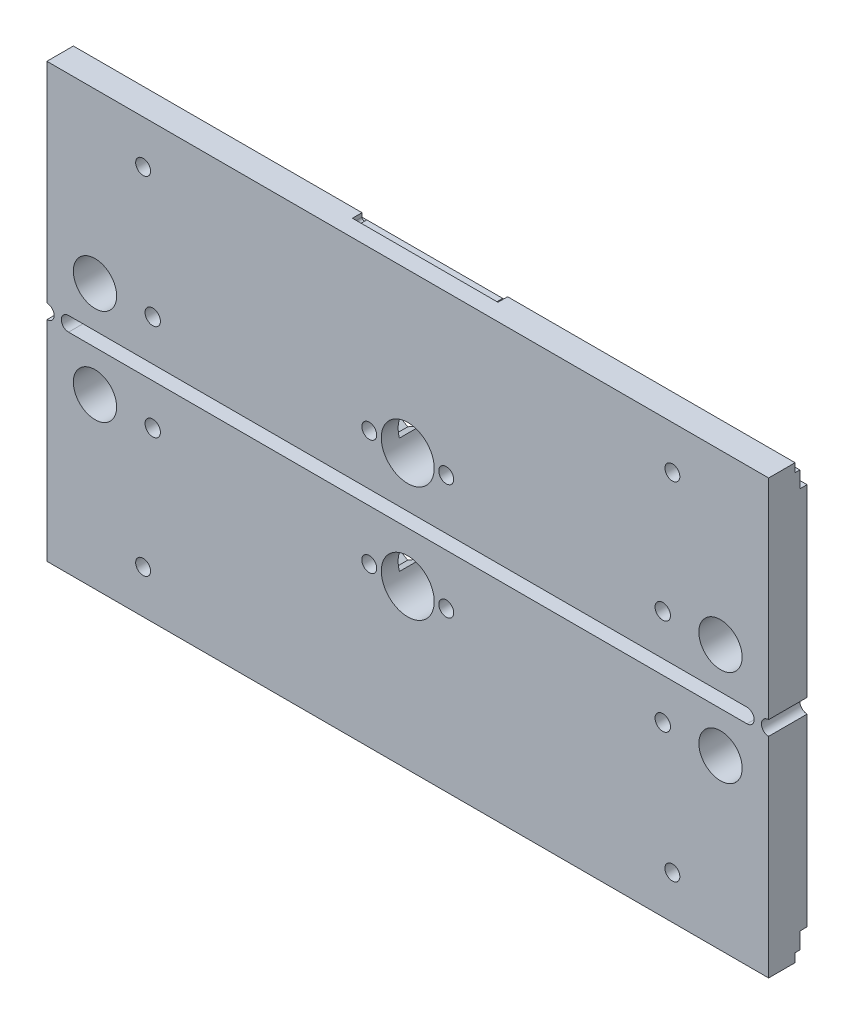
SolidWorks part; units mm, degrees
ref_plane "前视基准面" through (0, 0, 0) normal (0, 0, 1) x (1, 0, 0)
ref_plane "上视基准面" through (0, 0, 0) normal (0, 1, 0) x (1, 0, 0)
ref_plane "右视基准面" through (0, 0, 0) normal (1, 0, 0) x (0, 0, -1)
sketch "前视图草图" plane through (0, 0, 0) normal (0, 0, 1) x (1, 0, 0)
  line L0 (0, 0) -> (8.5179, 0) construction
  line L1 (0, 0) -> (0, 5.4227) construction
sketch "草图2" plane through (0, 0, 0) normal (0, 0, 1) x (1, 0, 0)
  line L0 (0, 0) -> (150, 0)
  line L1 (-200000, 0) -> (200008.5179, 0) construction
  line L2 (150, 0) -> (150, 43.5)
  line L3 (150, 43.5) -> (0, 43.5)
  line L4 (0, -200000) -> (0, 200005.4227) construction
  line L5 (0, 43.5) -> (0, 0)
  line L6 (75, 43.5) -> (75, 0) construction
  line L7 (10, 8.5) -> (140, 8.5) construction
  circle A0 centre (10, 8.5) radius 4.5
  circle A1 centre (75, 10.5) radius 4.05
  circle A2 centre (140, 8.5) radius 4.5
  dimension "D3" = 2
  dimension "D9" = 9
  dimension "D10" = 9
  dimension "D11" = 8.1
  dimension "D1" = 43.5
  dimension "D2" = 150
  dimension "D4" = 65
  dimension "D6" = 65
  dimension "D7" = 8.5
  dimension "D8" = 10
  dimension "D12" = 10
extrude "凸台-拉伸1" add sketch "草图2" along normal blind 8
sketch "草图3" plane through (0, 0, 8) normal (0, 0, 1) x (1, 0, 0)
  line L0 (16.088, 8) -> (31.4805, 8) construction
  line L1 (10, 8.5) -> (10, 17.3386) construction
  line L2 (140, 8.5) -> (140, 17.0917) construction
  line L4 (-200000, 0) -> (200008.5179, 0) construction
  circle A2 centre (26, 8) radius 2.55
  circle A3 centre (124, 8) radius 2.55
  dimension "D4" = 5.1
  dimension "D5" = 5.1
  dimension "D1" = 8
  dimension "D2" = 16
  dimension "D3" = 16
extrude "切除-拉伸1" [suppressed] cut sketch "草图3" against normal through all
sketch "草图4" plane through (150, 0, 0) normal (1, 0, 0) x (0, 0, -1)
  line L1 (0, -200000) -> (0, 200005.4227) construction
  line L2 (-1.5, 41.7) -> (-2.5, 41.7)
  line L3 (-2.5, 41.7) -> (-2.5, 43.5)
  line L4 (-8, 43.5) -> (0, 43.5) construction
  line L5 (-2.5, 43.5) -> (0, 43.5)
  line L6 (-1.5, 41.7) -> (-1.5, 38.3)
  line L7 (-1.5, 38.3) -> (0, 38.3)
  line L8 (0, 38.3) -> (0, 43.5)
  dimension "D1" = 3.4
  dimension "D2" = 2.5
  dimension "D3" = 1.5
  dimension "D4" = 1.8
extrude "切除-拉伸2" cut sketch "草图4" against normal through all
sketch "草图5" plane through (0, 0, 8) normal (0, 0, 1) x (1, 0, 0)
  line L0 (75, 10.5) -> (91.5376, 10.5) construction
  circle A0 centre (75, 10.5) radius 8 construction
  circle A1 centre (83, 10.5) radius 1.55
  circle A2 centre (67, 10.5) radius 1.55
  dimension "D1" = 3.1
  dimension "D2" = 3.1
  dimension "D3" = 16
extrude "切除-拉伸3" cut sketch "草图5" against normal through all
sketch "草图20" plane through (0, 0, 0) normal (0, 0, -1) x (-1, 0, 0)
  circle A0 centre (-75, 10.5) radius 5.5
  dimension "D1" = 11
extrude "切除-拉伸17" cut sketch "草图20" against normal through all
sketch "草图29" plane through (0, 0, 8) normal (0, 0, 1) x (1, 0, 0)
  line L0 (10, 8.5) -> (140, 8.5) construction
  line L1 (75, 10.5) -> (75, 8.5) construction
  circle A0 centre (22, 8.5) radius 1.6
  circle A1 centre (128, 8.5) radius 1.6
  dimension "D1" = 3.2
  dimension "D2" = 12
extrude "切除-拉伸18" cut sketch "草图29" against normal through all
sketch "草图7" [suppressed] plane through (0, 0, 0) normal (0, 0, -1) x (-1, 0, 0)
  line L0 (-40, 12) -> (-40, -8.3696) construction
  line L1 (-23, 10) -> (-23, -2.3368) construction
  line L2 (200000, 0) -> (-200008.5179, 0) construction
  line L6 (-27.05, 10) -> (-27.05, 2.5)
  line L7 (-29.55, 0) -> (-16.45, 0)
  line L8 (-18.95, 2.5) -> (-18.95, 10)
  line L9 (-23, 8) -> (-23, 15.9045) construction
  line L13 (0, -200000) -> (0, 200005.4227) construction
  line L14 (-57, 8) -> (-57, 15.9045) construction
  line L15 (-57, 10) -> (-57, -2.3368) construction
  line L16 (-61.05, 2.5) -> (-61.05, 10)
  line L17 (-50.45, 0) -> (-63.55, 0)
  line L18 (-52.95, 10) -> (-52.95, 2.5)
  arc A1 (-18.95, 10) -> (-27.05, 10) centre (-23, 10) ccw
  arc A4 (-29.55, 0) -> (-27.05, 2.5) centre (-29.55, 2.5) ccw
  arc A5 (-18.95, 2.5) -> (-16.45, 0) centre (-16.45, 2.5) ccw
  arc A7 (-61.05, 2.5) -> (-63.55, 0) centre (-63.55, 2.5) cw
  arc A8 (-50.45, 0) -> (-52.95, 2.5) centre (-50.45, 2.5) cw
  arc A9 (-61.05, 10) -> (-52.95, 10) centre (-57, 10) cw
  dimension "D1" = 40
  dimension "D4" = 8.1
  dimension "D7" = 2.5
  dimension "D8" = 2.5
  dimension "D3" = 10
extrude "切除-拉伸4" [suppressed] cut sketch "草图7" against normal blind 6
sketch "草图8" plane through (0, 0, 0) normal (0, 0, -1) x (-1, 0, 0)
  line L0 (-75, 10) -> (-92.3165, 10) construction
  line L2 (-65.5, 12.85) -> (-84.5, 12.85)
  line L3 (-84.5, 7.15) -> (-65.5, 7.15)
  line L4 (200000, 0) -> (-200008.5179, 0) construction
  line L5 (-150, 0) -> (-150, 38.3) construction
  line L6 (-80.15, 8.8546) -> (-80.15, 12.1454)
  line L7 (-80.15, 12.1454) -> (-83, 13.7909)
  line L8 (-83, 13.7909) -> (-85.85, 12.1454)
  line L9 (-85.85, 12.1454) -> (-85.85, 8.8546)
  line L10 (-85.85, 8.8546) -> (-83, 7.2091)
  line L11 (-83, 7.2091) -> (-80.15, 8.8546)
  line L12 (-64.15, 8.8546) -> (-64.15, 12.1454)
  line L13 (-64.15, 12.1454) -> (-67, 13.7909)
  line L14 (-67, 13.7909) -> (-69.85, 12.1454)
  line L15 (-69.85, 12.1454) -> (-69.85, 8.8546)
  line L16 (-69.85, 8.8546) -> (-67, 7.2091)
  line L17 (-67, 7.2091) -> (-64.15, 8.8546)
  line L18 (0, 43.5) -> (-150, 43.5) construction
  line L20 (-75, 43.5) -> (-75, 0) construction
  line L26 (-22, 5.2091) -> (-19.15, 6.8546)
  line L27 (-19.15, 6.8546) -> (-19.15, 10.1454)
  line L28 (-19.15, 10.1454) -> (-22, 11.7909)
  line L29 (-22, 11.7909) -> (-24.85, 10.1454)
  line L30 (-24.85, 10.1454) -> (-24.85, 6.8546)
  line L31 (-24.85, 6.8546) -> (-22, 5.2091)
  line L32 (-125.15, 6.8546) -> (-125.15, 10.1454)
  line L33 (-125.15, 10.1454) -> (-128, 11.7909)
  line L34 (-128, 11.7909) -> (-130.85, 10.1454)
  line L35 (-130.85, 10.1454) -> (-130.85, 6.8546)
  line L36 (-130.85, 6.8546) -> (-128, 5.2091)
  line L37 (-128, 5.2091) -> (-125.15, 6.8546)
  arc A0 (-65.5, 7.15) -> (-65.5, 12.85) centre (-65.5, 10) ccw
  arc A1 (-84.5, 12.85) -> (-84.5, 7.15) centre (-84.5, 10) ccw
  circle A2 centre (-83, 10.5) radius 2.85 construction
  circle A3 centre (-67, 10.5) radius 2.85 construction
  circle A4 centre (-22, 8.5) radius 2.85 construction
  circle A5 centre (-128, 8.5) radius 2.85 construction
  dimension "D1" = 5.7
  dimension "D2" = 9.5
  dimension "D3" = 9.5
  dimension "D4" = 10
  dimension "D5" = 5.7
extrude "切除-拉伸5" cut sketch "草图8" against normal blind 4.5 contours L9 L10 L11 L6 L7 L8 | L17 L12 L13 L14 L15 L16 | L32 L33 L34 L35 L36 L37 | L26 L27 L28 L29 L30 L31
sketch "草图25" plane through (0, 0, 0) normal (0, 0, -1) x (-1, 0, 0)
  line L0 (-51.4471, 34.5) -> (-40.1512, 34.5) construction
  line L1 (-130, 37.1428) -> (-130, 21.9179) construction
  line L2 (-20, 37.1428) -> (-20, 21.9179) construction
  line L3 (0, 43.5) -> (-150, 43.5) construction
  line L6 (-75, 43.5) -> (-75, 0) construction
  line L7 (0, 43.5) -> (-150, 43.5) construction
  line L8 (200000, 0) -> (-200008.5179, 0) construction
  circle A0 centre (-130, 34.5) radius 1.55
  circle A1 centre (-20, 34.5) radius 1.55
  dimension "D4" = 3.1
  dimension "D5" = 3.1
  dimension "D1" = 9
  dimension "D2" = 55
  dimension "D3" = 55
extrude "切除-拉伸13" cut sketch "草图25" against normal through all
sketch "草图19" plane through (0, 0, 2.5) normal (0, 0, -1) x (-1, 0, 0)
  line L0 (0, 43.5) -> (-150, 43.5) construction
  line L1 (-60, 43.5) -> (-90.2479, 43.5)
  line L2 (-60, 43.5) -> (-60, 42.7)
  line L3 (-61, 42.7) -> (-89.2479, 42.7)
  line L4 (-90.2479, 43.5) -> (-90.2479, 42.7)
  line L6 (-90.2479, 81.6491) -> (-90.2479, -28.0472) construction
  line L7 (0, 41.7) -> (-150, 41.7) construction
  line L8 (-56.3335, 42.2) -> (-52.9089, 42.2) construction
  line L9 (-90.2479, 1029.0823) -> (-90.2479, 42.7) construction
  line L10 (-60, 1029.0823) -> (-60, 42.2) construction
  line L11 (-90.2479, 42.2) -> (-90.2479, -972.8) construction
  line L12 (-60, 42.2) -> (-60, -972.8) construction
  arc A3 (-90.2479, 42.7) -> (-89.2479, 42.7) centre (-89.7479, 42.7) ccw
  arc A6 (-61, 42.7) -> (-60, 42.7) centre (-60.5, 42.7) ccw
  dimension "D3" = 1
  dimension "D4" = 1
  dimension "D5" = 30.2479
  dimension "D6" = 15
  dimension "D2" = 0.8
  dimension "D1" = 0.5
extrude "切除-拉伸11" cut sketch "草图19" against normal blind 2
sketch "草图27" plane through (0, 0, 0) normal (0, 0, -1) x (-1, 0, 0)
  line L0 (-136, 38.3) -> (-136, 0) construction
  line L1 (-75, 38.3) -> (-75, 10.5) construction
  line L2 (0, 38.3) -> (-150, 38.3) construction
  line L3 (-150, 12.5) -> (0, 12.5) construction
  line L4 (-150, 0) -> (-150, 38.3) construction
  line L5 (0, -200000) -> (0, 200005.4227) construction
  line L6 (200000, 0) -> (-200008.5179, 0) construction
  line L9 (0, 38.3) -> (-150, 38.3) construction
  circle A0 centre (-136, 12.5) radius 1.55
  circle A4 centre (-140, 8.5) radius 4.5 construction
  circle A5 centre (-140, 8.5) radius 4.5 construction
  circle A6 centre (-14, 12.5) radius 1.55
  dimension "D5" = 3.1
  dimension "D1" = 4
  dimension "D2" = 14
extrude "切除-拉伸15" [suppressed] cut sketch "草图27" against normal through all
sketch "草图22" plane through (0, 0, 8) normal (0, 0, 1) x (1, 0, 0)
  line L1 (0, -200000) -> (0, 200005.4227) construction
  line L2 (0, -3) -> (4.5, -3)
  line L4 (150, 0) -> (145.5, 0)
  line L5 (3, 1.9875) -> (3, -4.1402) construction
  line L6 (147, -11.5647) -> (147, -5.1636) construction
  line L7 (150, 0) -> (150, 43.5) construction
  line L8 (145.5, -3) -> (150, -3)
  line L9 (4.5, 0) -> (0, 0)
  line L10 (148.5, -2.9635) -> (148.5, -4.3032) construction
  line L11 (1.5, -8.393) -> (1.5, -15.1693) construction
  arc A0 (4.5, 0) -> (4.5, -3) centre (4.5, -1.5) ccw
  arc A1 (145.5, -3) -> (145.5, 0) centre (145.5, -1.5) ccw
  arc A2 (0, -3) -> (0, 0) centre (0, -1.5) ccw
  arc A3 (150, 0) -> (150, -3) centre (150, -1.5) ccw
  dimension "D1" = 3
  dimension "D2" = 3
  dimension "D3" = 3
  dimension "D4" = 1.5
  dimension "D5" = 1.5
extrude "凸台-拉伸2" add sketch "草图22" against normal blind 8
ref_plane "基准面1" through (0, -1.5, 0) normal (0, -1, 0) x (-1, 0, 0)
mirror "镜向2" about plane through (0, -1.5, 0) normal (0, -1, 0) of "切除-拉伸18", "切除-拉伸17", "切除-拉伸13", "切除-拉伸11", "切除-拉伸5", "切除-拉伸2", "凸台-拉伸1", "切除-拉伸3"
sketch "草图23" plane through (0, 0, 0) normal (0, 0, -1) x (-1, 0, 0)
  line L0 (-80, 0) -> (0, 0)
  line L1 (0, 0) -> (0, -4)
  line L2 (0, -4) -> (-80, -4)
  line L3 (-80, -4) -> (-80, 0)
sketch "草图26" [suppressed] plane through (0, 0, 0) normal (0, 0, -1) x (-1, 0, 0)
  circle A0 centre (-148, -11.8) radius 6.025
  circle A1 centre (-12, -11.8) radius 6.025
  dimension "D1" = 12.05
  dimension "D2" = 12.05
extrude "切除-拉伸14" [suppressed] cut sketch "草图26" against normal through all
sketch "草图28" [suppressed] plane through (0, 0, 0) normal (0, 0, -1) x (-1, 0, 0)
  line L0 (-150, 0) -> (-150, 37.8) construction
  line L1 (-122.9, 5.6329) -> (-122.9, 10.3671)
  line L2 (-122.9, 10.3671) -> (-127, 12.7343)
  line L3 (-127, 12.7343) -> (-131.1, 10.3671)
  line L4 (-131.1, 10.3671) -> (-131.1, 5.6329)
  line L5 (-131.1, 5.6329) -> (-127, 3.2657)
  line L6 (-127, 3.2657) -> (-122.9, 5.6329)
  line L7 (-18.9, 5.6329) -> (-18.9, 10.3671)
  line L8 (-18.9, 10.3671) -> (-23, 12.7343)
  line L9 (-23, 12.7343) -> (-27.1, 10.3671)
  line L10 (-27.1, 10.3671) -> (-27.1, 5.6329)
  line L11 (-27.1, 5.6329) -> (-23, 3.2657)
  line L12 (-23, 3.2657) -> (-18.9, 5.6329)
  circle A0 centre (-127, 8) radius 4.1 construction
  circle A1 centre (-23, 8) radius 4.1 construction
  dimension "D1" = 8.2
extrude "切除-拉伸16" [suppressed] cut sketch "草图28" against normal blind 6
